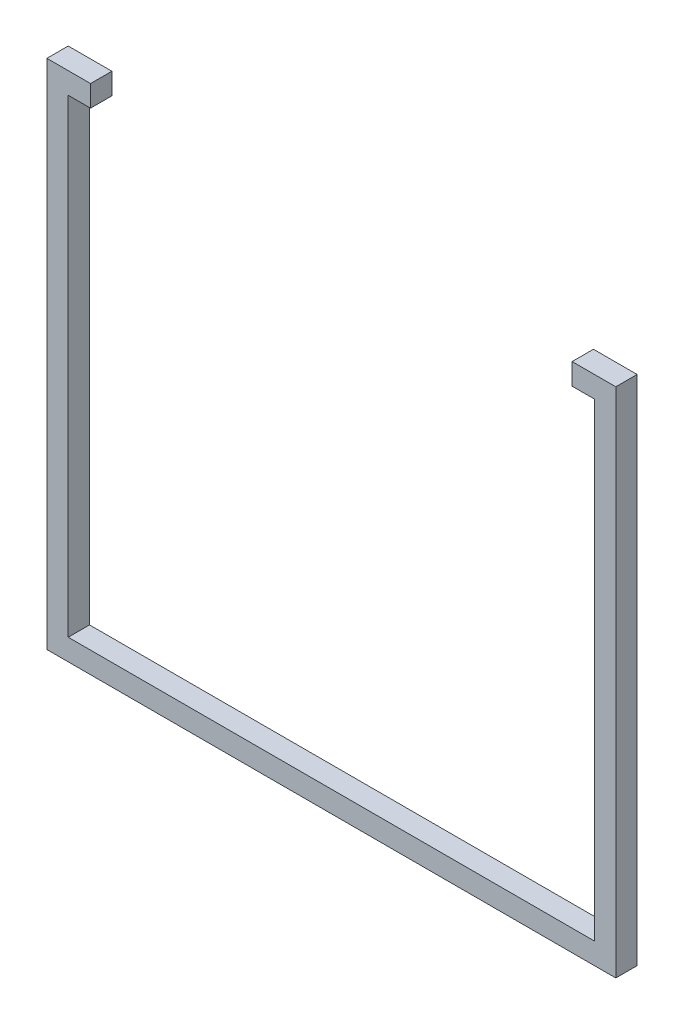
SolidWorks part; units mm, degrees
ref_plane "Front Plane" through (0, 0, 0) normal (0, 0, 1) x (1, 0, 0)
ref_plane "Top Plane" through (0, 0, 0) normal (0, 1, 0) x (1, 0, 0)
ref_plane "Right Plane" through (0, 0, 0) normal (1, 0, 0) x (0, 0, -1)
sketch "Sketch1" plane through (0, 0, 0) normal (0, 0, 1) x (1, 0, 0)
  line L0 (19.05, 438.15) -> (488.95, 438.15)
  line L1 (0, 0) -> (508, 0)
  line L2 (0, 0) -> (0, 457.2)
  line L3 (0, 457.2) -> (508, 457.2)
  line L4 (508, 0) -> (508, 457.2)
  line L5 (488.95, 19.05) -> (488.95, 438.15)
  line L6 (19.05, 19.05) -> (488.95, 19.05)
  line L7 (19.05, 19.05) -> (19.05, 438.15)
  dimension "D1" = 457.2
  dimension "D2" = 508
  dimension "D3" = 19.05
extrude "Boss-Extrude1" add sketch "Sketch1" along normal blind 19.05
sketch "Sketch2" plane through (0, 0, 19.05) normal (0, 0, 1) x (1, 0, 0)
  line L0 (254, 457.2) -> (254, 438.15) construction
  line L1 (508, 457.2) -> (0, 457.2) construction
  line L2 (488.95, 438.15) -> (19.05, 438.15) construction
  line L4 (39, 457.2) -> (469, 457.2)
  line L5 (39, 457.2) -> (39, 438.15)
  line L6 (39, 438.15) -> (469, 438.15)
  line L7 (469, 457.2) -> (469, 438.15)
  line L8 (39, 457.2) -> (469, 438.15) construction
  line L9 (39, 438.15) -> (469, 457.2) construction
  point P6 (254, 447.675)
  dimension "D1" = 430
extrude "Cut-Extrude1" cut sketch "Sketch2" against normal through all
